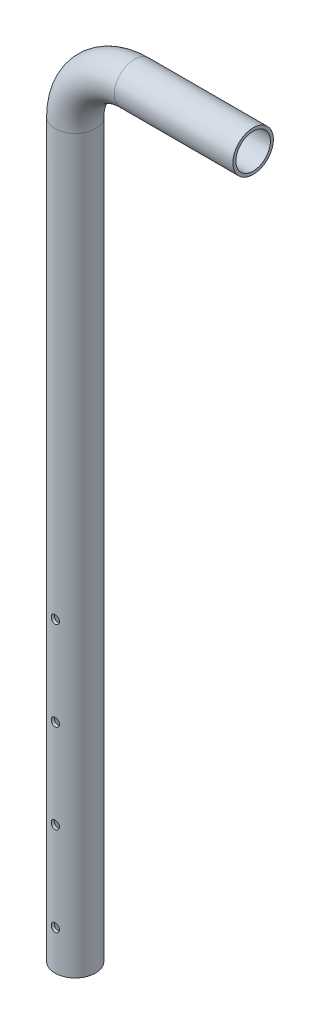
SolidWorks part; units mm, degrees
material "Alumina"
ref_plane "Plano frontal" through (0, 0, 0) normal (0, 0, 1) x (1, 0, 0)
ref_plane "Plano superior" through (0, 0, 0) normal (0, 1, 0) x (1, 0, 0)
ref_plane "Plano direito" through (0, 0, 0) normal (1, 0, 0) x (0, 0, -1)
sketch "Esboço1" plane through (0, 0, 0) normal (0, 0, 1) x (1, 0, 0)
  line L0 (0, 0) -> (0, 370)
  line L1 (30, 400) -> (90, 400)
  arc A0 (0, 370) -> (30, 400) centre (30, 370) cw
  point P6 (0, 400)
  dimension "D3" = 30
  dimension "D1" = 400
  dimension "D2" = 90
sketch "Esboço2" plane through (0, 0, 0) normal (0, 1, 0) x (1, 0, 0)
  circle A0 centre (0, 0) radius 10.25
  circle A1 centre (0, 0) radius 8.75
  dimension "D1" = 20.5
  dimension "D2" = 1.5
sweep "Varredura1" add profiles "Esboço2" path "Esboço1"
ref_plane "Plano1" through (0, 0, 11) normal (0, 0, 1) x (1, 0, 0)
hole_wizard "Furo roscado de M51" positions "Esboço4" profile "Esboço5" tap size "M5" standard "DIN" end condition through all
sketch "Esboço4" plane through (0, 0, 11) normal (0, 0, 1) x (1, 0, 0)
  line L0 (0, 0) -> (0, 88.6074) construction
  line L2 (-10.25, 0) -> (10.25, 0) construction
  point P0 (0, 20)
  dimension "D1" = 20
cosmetic thread "Rosca de furo1" parameters "D2"=5
sketch "Esboço5" plane through (0, 20, 11) normal (1, 0, 0) x (0, -1, 0)
  line L0 (0, 0) -> (0, 21.25)
  line L1 (0, 21.25) -> (2.1, 21.25)
  line L2 (2.1, 21.25) -> (2.1, 0)
  line L5 (2.1, 0) -> (0, 0)
  line L11 (0, -6.35) -> (0, 107.95) construction
  dimension "Thru Tap Drill Dia." = 4.2
  dimension "Thru Tap Drill Depth" = 21.25
sketch "Esboço6" plane through (0, 0, 11) normal (0, 0, 1) x (1, 0, 0)
  line L0 (0, 0) -> (0, 89.4322) construction
pattern_linear "Padrão linear1" count 4 spacing 45 along (0, 1, 0) of "Furo roscado de M51"
